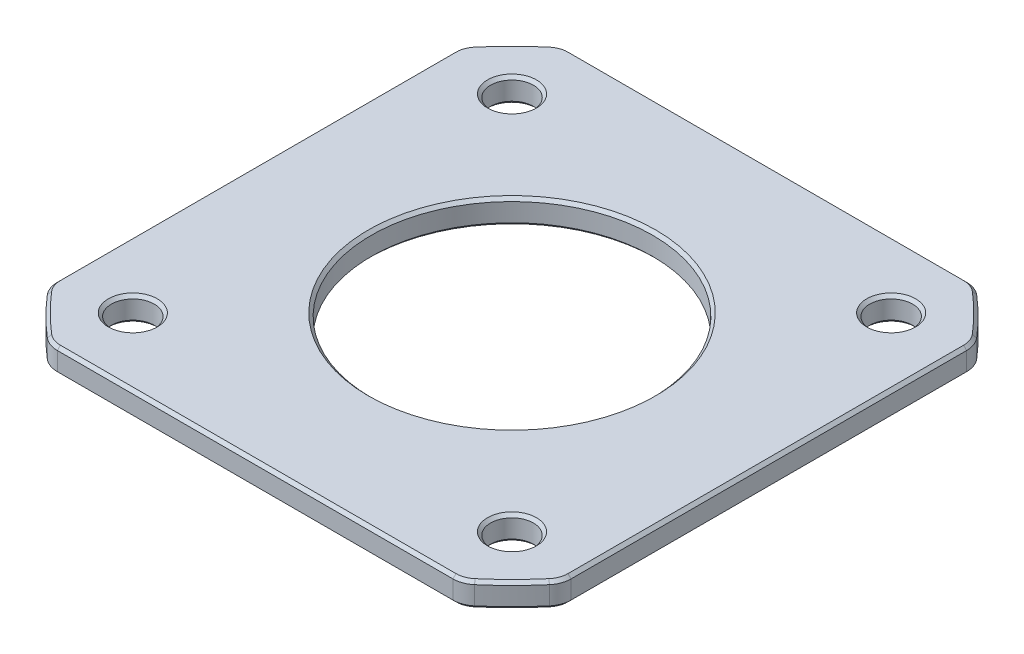
SolidWorks part; units mm, degrees
ref_plane "Front" through (0, 0, 0) normal (0, 0, 1) x (1, 0, 0)
ref_plane "Top" through (0, 0, 0) normal (0, 1, 0) x (1, 0, 0)
ref_plane "Right" through (0, 0, 0) normal (1, 0, 0) x (0, 0, -1)
sketch "Sketch1" plane through (0, 0, 0) normal (0, 1, 0) x (1, 0, 0)
  line L4 (16.171, -21) -> (-16.171, -21)
  line L5 (21, 16.171) -> (21, -16.171)
  line L6 (-16.171, 21) -> (16.171, 21)
  line L7 (-21, -16.171) -> (-21, 16.171)
  line L8 (0, 21) -> (0, 0) construction
  line L9 (0, 0) -> (21, 0) construction
  arc A12 (16.171, -21) -> (17.4673, -20.523) centre (16.171, -19) ccw
  arc A13 (17.4673, -20.523) -> (20.523, -17.4673) centre (0, 0) ccw
  arc A14 (20.523, -17.4673) -> (21, -16.171) centre (19, -16.171) ccw
  arc A15 (21, 16.171) -> (20.523, 17.4673) centre (19, 16.171) ccw
  arc A16 (20.523, 17.4673) -> (17.4673, 20.523) centre (0, 0) ccw
  arc A17 (17.4673, 20.523) -> (16.171, 21) centre (16.171, 19) ccw
  arc A18 (-16.171, 21) -> (-17.4673, 20.523) centre (-16.171, 19) ccw
  arc A19 (-17.4673, 20.523) -> (-20.523, 17.4673) centre (0, 0) ccw
  arc A20 (-20.523, 17.4673) -> (-21, 16.171) centre (-19, 16.171) ccw
  arc A21 (-21, -16.171) -> (-20.523, -17.4673) centre (-19, -16.171) ccw
  arc A22 (-20.523, -17.4673) -> (-17.4673, -20.523) centre (0, 0) ccw
  arc A23 (-17.4673, -20.523) -> (-16.171, -21) centre (-16.171, -19) ccw
  circle A25 centre (0, 0) radius 11.5
  circle A27 centre (15.5, -15.5) radius 1.75
  circle A29 centre (15.5, 15.5) radius 1.75
  circle A31 centre (-15.5, 15.5) radius 1.75
  circle A33 centre (-15.5, -15.5) radius 1.75
  dimension "D1" = 23
  dimension "D4" = 26.95
  dimension "D5" = 2
  dimension "D8" = 3.5
  dimension "D2" = 42
  dimension "D3" = 42
  dimension "D6" = 31
  dimension "D7" = 31
extrude "Boss-Extrude1" add sketch "Sketch1" along normal blind 2
chamfer "Chamfer1" distance 0.25 angle 45 42 edges at (-15.5, 0, 17.25) (-15.5, 0, -13.75) (15.5, 0, -13.75) (15.5, 0, 17.25) (0, 0, 11.5) (19.0565, 0, 19.0565) (20.877, 0, 16.8617) (21, 0, 0) (20.877, 0, -16.8617) (19.0565, 0, -19.0565) (16.8617, 0, -20.877) (0, 0, -21) (-16.8617, 0, -20.877) (-19.0565, 0, -19.0565) (-20.877, 0, -16.8617) (-21, 0, 0) (-20.877, 0, 16.8617) (-19.0565, 0, 19.0565) (-16.8617, 0, 20.877) (0, 0, 21) (16.8617, 0, 20.877) (-15.5, 2, 17.25) (15.5, 2, -13.75) (0, 2, 11.5) (0, 2, 21) (-16.8617, 2, 20.877) (-19.0565, 2, 19.0565) (-20.877, 2, 16.8617) (-21, 2, 0) (-20.877, 2, -16.8617) (-19.0565, 2, -19.0565) (-16.8617, 2, -20.877) (0, 2, -21) (16.8617, 2, -20.877) (19.0565, 2, -19.0565) (20.877, 2, -16.8617) (21, 2, 0) (20.877, 2, 16.8617) (19.0565, 2, 19.0565) (16.8617, 2, 20.877) (15.5, 2, 17.25) (-15.5, 2, -13.75)
